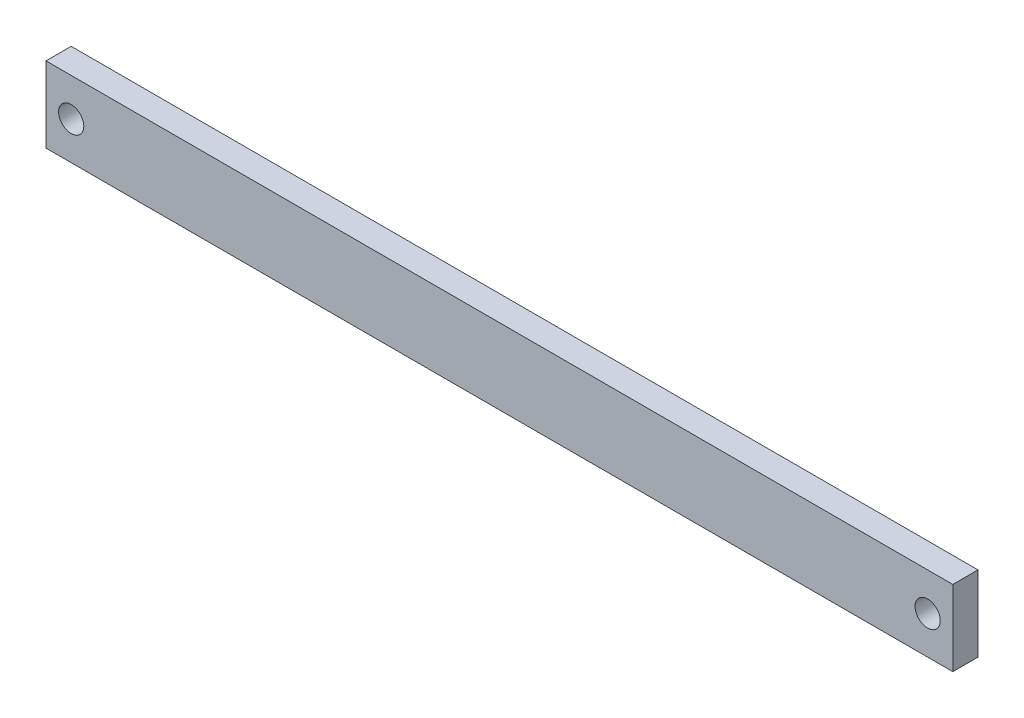
SolidWorks part; units mm, degrees
ref_plane "Front Plane" through (0, 0, 0) normal (0, 0, 1) x (1, 0, 0)
ref_plane "Top Plane" through (0, 0, 0) normal (0, 1, 0) x (1, 0, 0)
ref_plane "Right Plane" through (0, 0, 0) normal (1, 0, 0) x (0, 0, -1)
sketch "Sketch1" plane through (0, 0, 0) normal (0, 0, 1) x (1, 0, 0)
  line L1 (-90, -7.5) -> (90, -7.5)
  line L2 (-90, -7.5) -> (-90, 7.5)
  line L3 (-90, 7.5) -> (90, 7.5)
  line L4 (90, -7.5) -> (90, 7.5)
  line L5 (-90, -7.5) -> (90, 7.5) construction
  line L6 (-90, 7.5) -> (90, -7.5) construction
  circle A0 centre (85, 0) radius 2.5
  circle A1 centre (-85, 0) radius 2.5
  point P0 (0, 0)
  point P10 (0, 0)
  point P11 (-90, 0)
  point P12 (0, 0)
  point P13 (90, 0)
  point P14 (0, 0)
  dimension "D1" = 5
  dimension "D2" = 15
  dimension "D3" = 5
  dimension "D4" = 5
  dimension "D5" = 180
extrude "Boss-Extrude1" add sketch "Sketch1" along normal blind 5
equation "\"D4@Sketch1\"=\"D3@Sketch1\""
